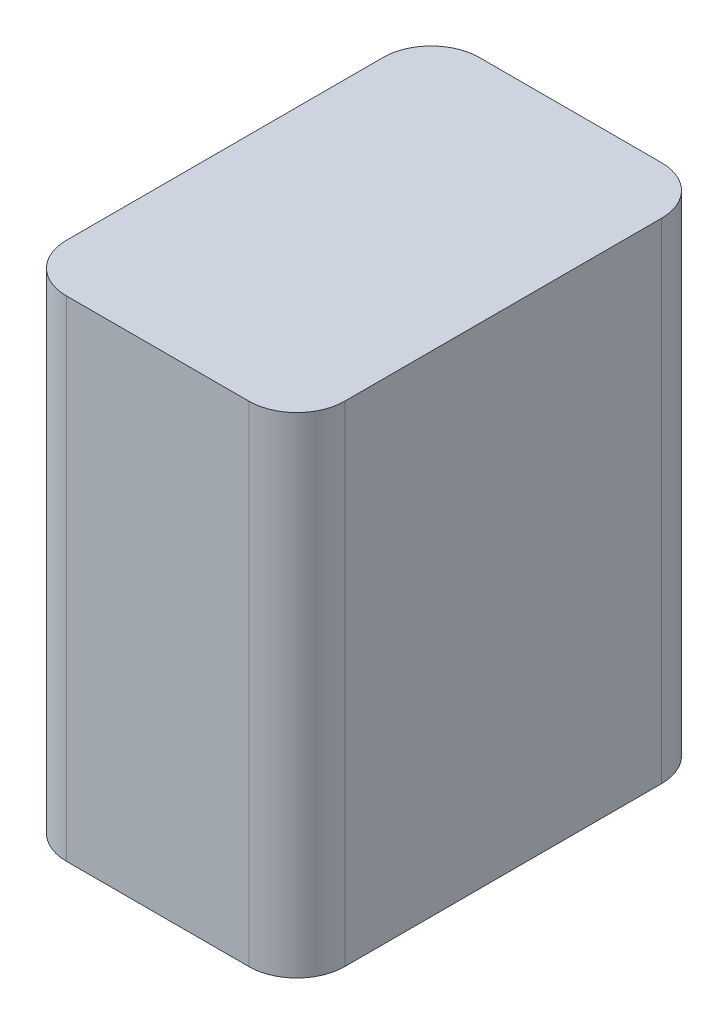
SolidWorks part; units mm, degrees
ref_plane "Front Plane" through (0, 0, 0) normal (0, 0, 1) x (1, 0, 0)
ref_plane "Top Plane" through (0, 0, 0) normal (0, 1, 0) x (1, 0, 0)
ref_plane "Right Plane" through (0, 0, 0) normal (1, 0, 0) x (0, 0, -1)
sketch "Sketch1" plane through (0, 0, 0) normal (0, 1, 0) x (1, 0, 0)
  line L1 (0, 0) -> (29, 0)
  line L2 (0, 0) -> (0, 43)
  line L3 (0, 43) -> (29, 43)
  line L4 (29, 0) -> (29, 43)
  dimension "D1" = 43
  dimension "D2" = 29
extrude "Boss-Extrude1" add sketch "Sketch1" along normal blind 51
fillet "Fillet1" radius 5 4 edges at (0, 25.5, -43) (29, 25.5, -43) (0, 25.5, 0) (29, 25.5, 0)
